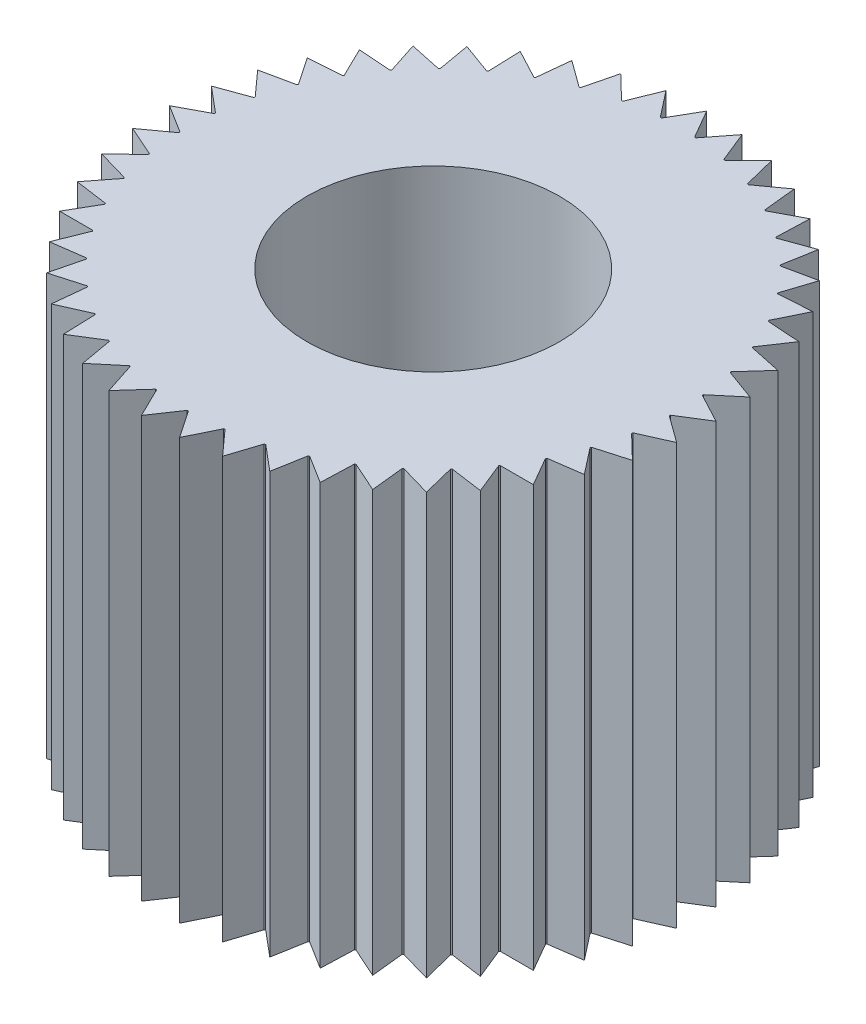
SolidWorks part; units mm, degrees
ref_plane "Front Plane" through (0, 0, 0) normal (0, 0, 1) x (1, 0, 0)
ref_plane "Top Plane" through (0, 0, 0) normal (0, 1, 0) x (1, 0, 0)
ref_plane "Right Plane" through (0, 0, 0) normal (1, 0, 0) x (0, 0, -1)
sketch "Sketch2" plane through (0, 0, 0) normal (0, 1, 0) x (1, 0, 0)
  line L0 (0.3447, 2.4524) -> (0.1605, 2.2167)
  line L1 (0, 2.4765) -> (-0.1496, 2.2175)
  line L2 (0.4567, 2.1751) -> (0.3447, 2.4524)
  line L3 (0.1496, 2.2175) -> (0, 2.4765)
  line L4 (0.6826, 2.3806) -> (0.4675, 2.1728)
  line L5 (0.755, 2.0903) -> (0.6826, 2.3806)
  line L6 (1.0073, 2.2624) -> (0.7653, 2.0866)
  line L7 (1.0385, 1.9649) -> (1.0073, 2.2624)
  line L8 (1.3123, 2.1002) -> (1.0482, 1.9598)
  line L9 (1.3019, 1.8013) -> (1.3123, 2.1002)
  line L10 (1.5919, 1.8971) -> (1.3108, 1.7948)
  line L11 (1.5399, 1.6025) -> (1.5919, 1.8971)
  line L12 (1.8404, 1.6571) -> (1.5478, 1.5949)
  line L13 (1.748, 1.3726) -> (1.8404, 1.6571)
  line L14 (2.0531, 1.3848) -> (1.7547, 1.364)
  line L15 (1.922, 1.116) -> (2.0531, 1.3848)
  line L16 (2.2259, 1.0856) -> (1.9275, 1.1065)
  line L17 (2.0586, 0.8377) -> (2.2259, 1.0856)
  line L18 (2.3553, 0.7653) -> (2.0627, 0.8275)
  line L19 (2.1551, 0.543) -> (2.3553, 0.7653)
  line L20 (2.4389, 0.43) -> (2.1578, 0.5323)
  line L21 (2.2097, 0.2378) -> (2.4389, 0.43)
  line L22 (2.475, 0.0864) -> (2.2109, 0.2269)
  line L23 (2.2213, -0.0721) -> (2.475, 0.0864)
  line L24 (2.4629, -0.2589) -> (2.2209, -0.0831)
  line L25 (2.1897, -0.3805) -> (2.4629, -0.2589)
  line L26 (2.4029, -0.5991) -> (2.1878, -0.3913)
  line L27 (2.1154, -0.6816) -> (2.4029, -0.5991)
  line L28 (2.2962, -0.9277) -> (2.112, -0.692)
  line L29 (2, -0.9693) -> (2.2962, -0.9277)
  line L30 (2.1447, -1.2382) -> (1.9952, -0.9792)
  line L31 (1.8456, -1.2382) -> (2.1447, -1.2382)
  line L32 (1.9515, -1.5247) -> (1.8395, -1.2474)
  line L33 (1.6553, -1.4831) -> (1.9515, -1.5247)
  line L34 (1.7203, -1.7814) -> (1.648, -1.4912)
  line L35 (1.4328, -1.699) -> (1.7203, -1.7814)
  line L36 (1.4557, -2.0035) -> (1.4244, -1.7061)
  line L37 (1.1824, -1.8819) -> (1.4557, -2.0035)
  line L38 (1.1626, -2.1866) -> (1.1731, -1.8877)
  line L39 (0.909, -2.0281) -> (1.1626, -2.1866)
  line L40 (0.847, -2.3271) -> (0.899, -2.0326)
  line L41 (0.6179, -2.1349) -> (0.847, -2.3271)
  line L42 (0.5149, -2.4224) -> (0.6073, -2.1379)
  line L43 (0.3147, -2.2001) -> (0.5149, -2.4224)
  line L44 (0.1728, -2.4705) -> (0.3039, -2.2016)
  line L46 (0.0055, -2.2225) -> (0.1728, -2.4705)
  line L47 (-0.1728, -2.4705) -> (-0.0055, -2.2225)
  line L48 (-0.3039, -2.2016) -> (-0.1728, -2.4705)
  line L49 (-0.5149, -2.4224) -> (-0.3147, -2.2001)
  line L50 (-0.6073, -2.1379) -> (-0.5149, -2.4224)
  line L51 (-0.847, -2.3271) -> (-0.6179, -2.1349)
  line L52 (-0.899, -2.0326) -> (-0.847, -2.3271)
  line L53 (-1.1626, -2.1866) -> (-0.909, -2.0281)
  line L54 (-1.1731, -1.8877) -> (-1.1626, -2.1866)
  line L55 (-1.4557, -2.0035) -> (-1.1824, -1.8819)
  line L56 (-1.4244, -1.7061) -> (-1.4557, -2.0035)
  line L57 (-1.7203, -1.7814) -> (-1.4328, -1.699)
  line L58 (-1.648, -1.4912) -> (-1.7203, -1.7814)
  line L59 (-1.9515, -1.5247) -> (-1.6553, -1.4831)
  line L60 (-1.8395, -1.2474) -> (-1.9515, -1.5247)
  line L61 (-2.1447, -1.2383) -> (-1.8456, -1.2383)
  line L62 (-1.9952, -0.9792) -> (-2.1447, -1.2383)
  line L63 (-2.2962, -0.9277) -> (-2, -0.9693)
  line L64 (-2.112, -0.692) -> (-2.2962, -0.9277)
  line L65 (-2.4029, -0.5991) -> (-2.1154, -0.6816)
  line L66 (-2.1878, -0.3913) -> (-2.4029, -0.5991)
  line L67 (-2.4629, -0.2589) -> (-2.1897, -0.3805)
  line L68 (-2.2209, -0.0831) -> (-2.4629, -0.2589)
  line L69 (-2.475, 0.0864) -> (-2.2213, -0.0721)
  line L70 (-2.2109, 0.2269) -> (-2.475, 0.0864)
  line L71 (-2.4389, 0.43) -> (-2.2097, 0.2378)
  line L72 (-2.1578, 0.5323) -> (-2.4389, 0.43)
  line L73 (-2.3553, 0.7653) -> (-2.1551, 0.543)
  line L74 (-2.0627, 0.8275) -> (-2.3553, 0.7653)
  line L75 (-2.2259, 1.0856) -> (-2.0586, 0.8377)
  line L76 (-1.9275, 1.1065) -> (-2.2259, 1.0856)
  line L77 (-2.0531, 1.3848) -> (-1.922, 1.116)
  line L78 (-1.7547, 1.364) -> (-2.0531, 1.3848)
  line L79 (-1.8404, 1.6571) -> (-1.748, 1.3726)
  line L80 (-1.5478, 1.5949) -> (-1.8404, 1.6571)
  line L81 (-1.5919, 1.8971) -> (-1.5399, 1.6025)
  line L82 (-1.3108, 1.7948) -> (-1.5919, 1.8971)
  line L83 (-1.3123, 2.1002) -> (-1.3019, 1.8013)
  line L84 (-1.0482, 1.9598) -> (-1.3123, 2.1002)
  line L85 (-1.0073, 2.2624) -> (-1.0385, 1.9649)
  line L86 (-0.7653, 2.0866) -> (-1.0073, 2.2624)
  line L87 (-0.6826, 2.3806) -> (-0.755, 2.0903)
  line L88 (-0.4675, 2.1728) -> (-0.6826, 2.3806)
  line L89 (-0.3447, 2.4524) -> (-0.4567, 2.1751)
  line L90 (-0.1605, 2.2167) -> (-0.3447, 2.4524)
  arc A0 (-0.1496, 2.2175) -> (-0.1605, 2.2167) centre (0, 0) ccw
  circle A1 centre (0, 2.2225) radius 0.127 construction
  arc A2 (0.1605, 2.2167) -> (0.1496, 2.2175) centre (0, 0) ccw
  arc A3 (0.4675, 2.1728) -> (0.4567, 2.1751) centre (0, 0) ccw
  arc A4 (0.7653, 2.0866) -> (0.755, 2.0903) centre (0, 0) ccw
  arc A5 (1.0482, 1.9598) -> (1.0385, 1.9649) centre (0, 0) ccw
  arc A6 (1.3108, 1.7948) -> (1.3019, 1.8013) centre (0, 0) ccw
  arc A7 (1.5478, 1.5949) -> (1.5399, 1.6025) centre (0, 0) ccw
  arc A8 (1.7547, 1.364) -> (1.748, 1.3726) centre (0, 0) ccw
  arc A9 (1.9275, 1.1065) -> (1.922, 1.116) centre (0, 0) ccw
  arc A10 (-0.4567, 2.1751) -> (-0.4675, 2.1728) centre (0, 0) ccw
  arc A11 (-0.755, 2.0903) -> (-0.7653, 2.0866) centre (0, 0) ccw
  arc A12 (-1.0385, 1.9649) -> (-1.0482, 1.9598) centre (0, 0) ccw
  arc A13 (-1.3019, 1.8013) -> (-1.3108, 1.7948) centre (0, 0) ccw
  arc A14 (-1.5399, 1.6025) -> (-1.5478, 1.5949) centre (0, 0) ccw
  arc A15 (-1.748, 1.3726) -> (-1.7547, 1.364) centre (0, 0) ccw
  arc A16 (-1.922, 1.116) -> (-1.9275, 1.1065) centre (0, 0) ccw
  arc A17 (-2.0586, 0.8377) -> (-2.0627, 0.8275) centre (0, 0) ccw
  arc A18 (-2.1551, 0.543) -> (-2.1578, 0.5323) centre (0, 0) ccw
  arc A19 (-2.2097, 0.2378) -> (-2.2109, 0.2269) centre (0, 0) ccw
  arc A20 (-2.2213, -0.0721) -> (-2.2209, -0.0831) centre (0, 0) ccw
  arc A21 (2.0627, 0.8275) -> (2.0586, 0.8377) centre (0, 0) ccw
  arc A22 (2.1578, 0.5323) -> (2.1551, 0.543) centre (0, 0) ccw
  arc A23 (2.2109, 0.2269) -> (2.2097, 0.2378) centre (0, 0) ccw
  arc A24 (2.2209, -0.0831) -> (2.2213, -0.0721) centre (0, 0) ccw
  arc A25 (2.1878, -0.3913) -> (2.1897, -0.3805) centre (0, 0) ccw
  arc A26 (2.112, -0.692) -> (2.1154, -0.6816) centre (0, 0) ccw
  arc A27 (1.9952, -0.9792) -> (2, -0.9693) centre (0, 0) ccw
  arc A28 (1.8395, -1.2474) -> (1.8456, -1.2382) centre (0, 0) ccw
  arc A29 (1.648, -1.4912) -> (1.6553, -1.4831) centre (0, 0) ccw
  arc A30 (1.4244, -1.7061) -> (1.4328, -1.699) centre (0, 0) ccw
  arc A31 (1.1731, -1.8877) -> (1.1824, -1.8819) centre (0, 0) ccw
  arc A32 (0.899, -2.0326) -> (0.909, -2.0281) centre (0, 0) ccw
  arc A33 (0.6073, -2.1379) -> (0.6179, -2.1349) centre (0, 0) ccw
  arc A34 (0.3039, -2.2016) -> (0.3147, -2.2001) centre (0, 0) ccw
  arc A35 (-0.0055, -2.2225) -> (0.0055, -2.2225) centre (0, 0) ccw
  arc A36 (-0.3147, -2.2001) -> (-0.3039, -2.2016) centre (0, 0) ccw
  arc A37 (-0.6179, -2.1349) -> (-0.6073, -2.1379) centre (0, 0) ccw
  arc A38 (-0.909, -2.0281) -> (-0.899, -2.0326) centre (0, 0) ccw
  arc A39 (-1.1824, -1.8819) -> (-1.1731, -1.8877) centre (0, 0) ccw
  arc A40 (-1.4328, -1.699) -> (-1.4244, -1.7061) centre (0, 0) ccw
  arc A41 (-1.6553, -1.4831) -> (-1.648, -1.4912) centre (0, 0) ccw
  arc A42 (-1.8456, -1.2383) -> (-1.8395, -1.2474) centre (0, 0) ccw
  arc A43 (-2, -0.9693) -> (-1.9952, -0.9792) centre (0, 0) ccw
  arc A44 (-2.1154, -0.6816) -> (-2.112, -0.692) centre (0, 0) ccw
  arc A45 (-2.1897, -0.3805) -> (-2.1878, -0.3913) centre (0, 0) ccw
extrude "Boss-Extrude1" add sketch "Sketch2" along normal blind 3.81
sketch "Sketch4" plane through (0, 3.81, 0) normal (0, 1, 0) x (1, 0, 0)
  circle A0 centre (0, 0) radius 1.143
  dimension "D1" = 2.286
extrude "Cut-Extrude2" cut sketch "Sketch4" against normal blind 2.286
sketch "Sketch5" plane through (0, 0, 0) normal (0, -1, 0) x (1, 0, 0)
  circle A0 centre (0, 0) radius 0.635
  dimension "D1" = 1.27
extrude "Cut-Extrude3" cut sketch "Sketch5" against normal blind 1.27
scale "Scale1" bodies to scale 105 scale about centroid uniform scaling yes scale factor 1.5
